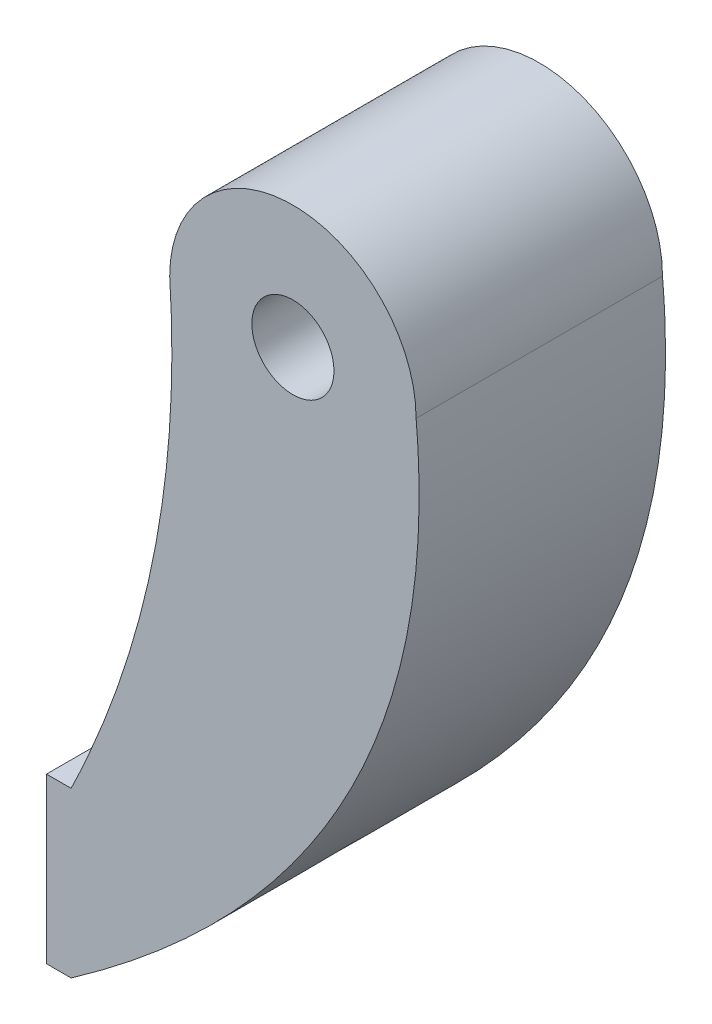
SolidWorks part; units mm, degrees
ref_plane "Front Plane" through (0, 0, 0) normal (0, 0, 1) x (1, 0, 0)
ref_plane "Top Plane" through (0, 0, 0) normal (0, 1, 0) x (1, 0, 0)
ref_plane "Right Plane" through (0, 0, 0) normal (1, 0, 0) x (0, 0, -1)
sketch "Sketch1" plane through (0, 0, 0) normal (0, 0, 1) x (1, 0, 0)
  line L0 (-15, -40) -> (-13.5, -40)
  line L1 (-15, -40) -> (-15, -30)
  line L2 (-15, -30) -> (-13.5, -30)
  arc A0 (7.5, 0) -> (-7.5, 0) centre (0, 0) ccw
  spline S0 degree 2 poles (7.5, 0) (9.6638, -23.7748) (-13.5, -40) knots 0 0 0 1 1 1
  spline S1 degree 2 poles (-7.5, 0) (-6.4643, -15.5382) (-13.5, -30) knots 0 0 0 1 1 1
  point P3 (-15, -40)
  dimension "D1" = 15
  dimension "D7" = 1.5
  dimension "D2" = 15
  dimension "D3" = 40
  dimension "D4" = 1.5
  dimension "D5" = 10
extrude "Boss-Extrude1" add sketch "Sketch1" along normal blind 15
sketch "Sketch2" plane through (0, 0, 15) normal (0, 0, 1) x (1, 0, 0)
  circle A0 centre (0, 0) radius 2.5
  dimension "D1" = 5
extrude "Cut-Extrude1" cut sketch "Sketch2" against normal through all both and the other way through all
